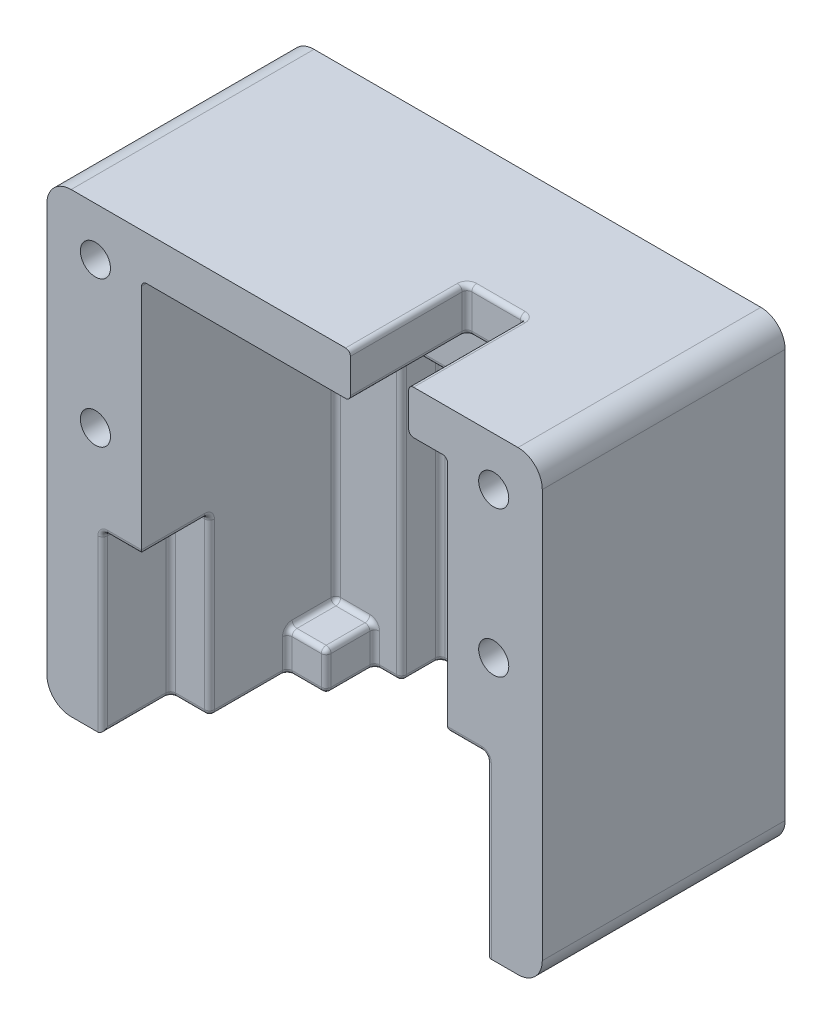
SolidWorks part; units mm, degrees
ref_plane "Front Plane" through (0, 0, 0) normal (0, 0, 1) x (1, 0, 0)
ref_plane "Top Plane" through (0, 0, 0) normal (0, 1, 0) x (1, 0, 0)
ref_plane "Right Plane" through (0, 0, 0) normal (1, 0, 0) x (0, 0, -1)
sketch "Sketch1" plane through (0, 0, 0) normal (0, 0, 1) x (1, 0, 0)
  line L0 (0, 0) -> (51, 0)
  line L1 (51, 0) -> (51, 47)
  line L2 (51, 47) -> (0, 47)
  line L3 (0, 47) -> (0, 0)
  dimension "D1" = 51
  dimension "D2" = 47
extrude "Boss-Extrude1" add sketch "Sketch1" along normal blind 5
sketch "Sketch2" plane through (0, 0, 5) normal (0, 0, 1) x (1, 0, 0)
  line L0 (0, 0) -> (0, 47)
  line L1 (0, 47) -> (51, 47)
  line L2 (51, 47) -> (51, 0)
  line L3 (51, 0) -> (41.25, 0)
  line L4 (0, 0) -> (51, 0) construction
  line L5 (41.25, 0) -> (41.25, 42.5)
  line L6 (41.25, 42.5) -> (9.75, 42.5)
  line L7 (9.75, 42.5) -> (9.75, 0)
  line L8 (9.75, 0) -> (0, 0)
  dimension "D1" = 9.75
  dimension "D2" = 9.75
  dimension "D3" = 4.5
extrude "Boss-Extrude2" add sketch "Sketch2" along normal blind 20
sketch "Sketch4" plane through (0, 0, 5) normal (0, 0, 1) x (1, 0, 0)
  line L0 (41.25, 0) -> (37.25, 0)
  line L1 (9.75, 0) -> (41.25, 0) construction
  line L2 (37.25, 0) -> (37.25, 4)
  line L3 (37.25, 4) -> (41.25, 4)
  line L4 (41.25, 42.5) -> (41.25, 0) construction
  line L5 (41.25, 4) -> (41.25, 0)
  line L6 (9.75, 0) -> (13.75, 0)
  line L7 (13.75, 0) -> (13.75, 4)
  line L8 (13.75, 4) -> (9.75, 4)
  line L9 (9.75, 0) -> (9.75, 42.5) construction
  line L10 (9.75, 4) -> (9.75, 0)
  dimension "D1" = 4
  dimension "D2" = 4
  dimension "D3" = 4
  dimension "D4" = 4
extrude "Boss-Extrude3" add sketch "Sketch4" along normal blind 5
sketch "Sketch5" plane through (0, 0, 25) normal (0, 0, 1) x (1, 0, 0)
  line L0 (41.25, 0) -> (41.25, 18)
  line L1 (41.25, 42.5) -> (41.25, 4) construction
  line L2 (41.25, 18) -> (45.25, 18)
  line L3 (45.25, 18) -> (45.25, 0)
  line L4 (41.25, 0) -> (51, 0) construction
  line L5 (45.25, 0) -> (41.25, 0)
  line L6 (9.75, 0) -> (9.75, 18)
  line L7 (9.75, 4) -> (9.75, 42.5) construction
  line L8 (9.75, 18) -> (5.75, 18)
  line L9 (5.75, 18) -> (5.75, 0)
  line L10 (0, 0) -> (9.75, 0) construction
  line L11 (5.75, 0) -> (9.75, 0)
  dimension "D1" = 4
  dimension "D2" = 18
  dimension "D3" = 18
  dimension "D4" = 4
extrude "Cut-Extrude1" cut sketch "Sketch5" against normal blind 7
sketch "Sketch7" plane through (0, 0, 25) normal (0, 0, 1) x (1, 0, 0)
  line L0 (37.25, 47) -> (37.25, 42.5)
  line L1 (51, 47) -> (0, 47) construction
  line L2 (9.75, 42.5) -> (41.25, 42.5) construction
  line L3 (37.25, 42.5) -> (31.25, 42.5)
  line L4 (9.75, 42.5) -> (41.25, 42.5) construction
  line L5 (31.25, 42.5) -> (31.25, 47)
  line L6 (31.25, 47) -> (37.25, 47)
  line L7 (41.25, 42.5) -> (41.25, 18) construction
  dimension "D1" = 4
  dimension "D2" = 6
extrude "Cut-Extrude2" cut sketch "Sketch7" against normal blind 12
sketch "Sketch8" plane through (0, 0, 5) normal (0, 0, 1) x (1, 0, 0)
  line L0 (25.5, 0) -> (34.5, 0)
  line L1 (13.75, 0) -> (37.25, 0) construction
  line L2 (34.5, 0) -> (34.5, 30)
  line L3 (34.5, 30) -> (16.5, 30)
  line L4 (16.5, 30) -> (16.5, 0)
  line L5 (16.5, 0) -> (25.5, 0)
  dimension "D1" = 9
  dimension "D2" = 9
  dimension "D3" = 30
extrude "Cut-Extrude3" cut sketch "Sketch8" against normal blind 4
sketch "Sketch9" plane through (0, 0, 25) normal (0, 0, 1) x (1, 0, 0)
  line L0 (0, 47) -> (0, 0) construction
  line L1 (31.25, 47) -> (0, 47) construction
  line L2 (51, 47) -> (37.25, 47) construction
  line L3 (51, 0) -> (51, 47) construction
  circle A0 centre (5, 27) radius 1.55
  circle A1 centre (5, 42) radius 1.55
  circle A2 centre (46, 42) radius 1.55
  circle A3 centre (46, 27) radius 1.55
  dimension "D1" = 3.1
  dimension "D2" = 3.1
  dimension "D3" = 3.1
  dimension "D4" = 3.1
  dimension "D5" = 15
  dimension "D6" = 15
  dimension "D7" = 5
  dimension "D8" = 5
  dimension "D9" = 5
  dimension "D10" = 5
extrude "Cut-Extrude4" cut sketch "Sketch9" against normal blind 10
sketch "Sketch10" plane through (0, 0, 5) normal (0, 0, 1) x (1, 0, 0)
  line L0 (9.75, 4) -> (9.75, 42.5) construction
  line L2 (41.25, 42.5) -> (41.25, 4) construction
  line L3 (9.75, 42.5) -> (41.25, 42.5) construction
  circle A0 centre (17.5, 34.5) radius 1.75
  circle A1 centre (33.5, 34.5) radius 1.75
  dimension "D1" = 3.5
  dimension "D2" = 3.5
  dimension "D3" = 7.75
  dimension "D4" = 7.75
  dimension "D5" = 8
extrude "Cut-Extrude5" cut sketch "Sketch10" against normal through all
sketch "Sketch11" plane through (0, 0, 5) normal (0, 0, 1) x (1, 0, 0)
  circle A0 centre (17.5, 34.5) radius 2.5
  circle A1 centre (33.5, 34.5) radius 2.5
  dimension "D1" = 5
  dimension "D2" = 5
extrude "Cut-Extrude6" cut sketch "Sketch11" against normal blind 2
fillet "Fillet1" radius 0.5 62 edges at (9.75, 4, 7.5) (9.75, 0, 14) (5.75, 0, 21.5) (16.5, 0, 3) (34.5, 0, 3) (41.25, 4, 7.5) (45.25, 0, 21.5) (37.25, 42.5, 19) (37.25, 47, 19) (31.25, 42.5, 19) (31.25, 47, 19) (9.75, 18, 21.5) (5.75, 18, 21.5) (7.75, 18, 25) (45.25, 18, 21.5) (41.25, 18, 21.5) (43.25, 18, 25) (13.75, 0, 7.5) (13.75, 4, 7.5) (11.75, 4, 10) (13.75, 2, 10) (11.75, 0, 10) (9.75, 2, 10) (5.75, 9, 18) (7.75, 18, 18) (9.75, 9, 18) (7.75, 0, 18) (15.125, 0, 5) (13.75, 2, 5) (11.75, 4, 5) (9.75, 23.25, 5) (25.5, 42.5, 5) (41.25, 23.25, 5) (39.25, 4, 5) (35.875, 0, 5) (34.5, 15, 5) (25.5, 30, 5) (16.5, 15, 5) (16.5, 15, 1) (25.5, 30, 1) (34.5, 15, 1) (25.5, 0, 1) (37.25, 4, 7.5) (37.25, 0, 7.5) (37.25, 2, 5) (39.25, 0, 10) (37.25, 2, 10) (39.25, 4, 10) (41.25, 2, 10) (41.25, 9, 18) (43.25, 18, 18) (45.25, 9, 18) (43.25, 0, 18) (37.25, 44.75, 13) (34.25, 42.5, 13) (31.25, 44.75, 13) (34.25, 47, 13) (41.25, 42.5, 15) (9.75, 42.5, 15) (41.25, 0, 14) (45.25, 9, 25) (5.75, 9, 25)
fillet "Fillet2" radius 2.5 4 edges at (0, 47, 12.5) (51, 47, 12.5) (51, 0, 12.5) (0, 0, 12.5)
